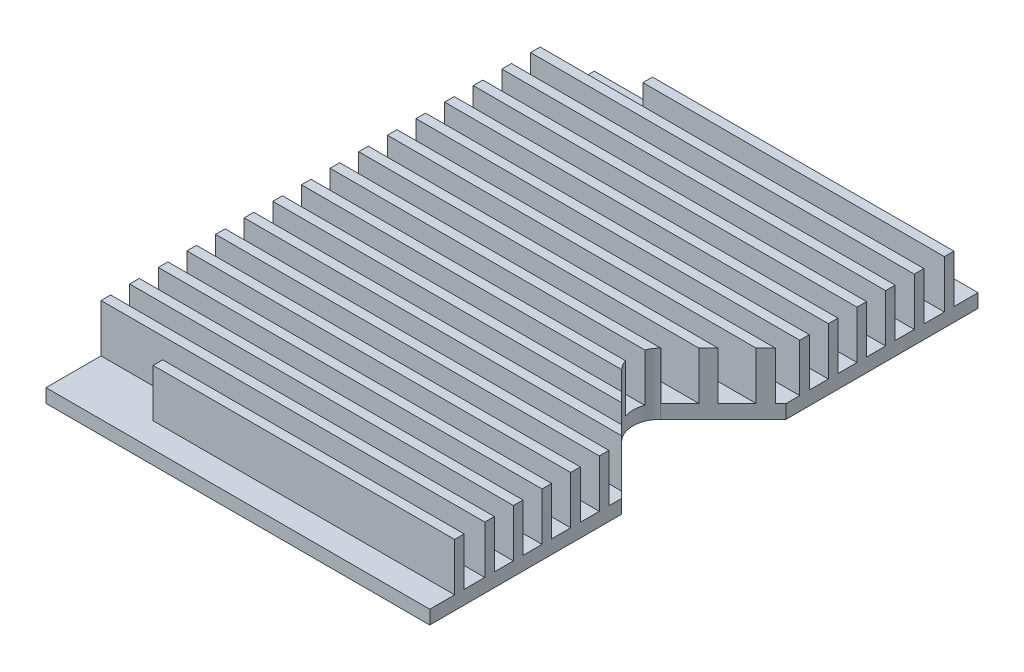
SolidWorks part; units mm, degrees
material "铜"
ref_plane "前视基准面" through (0, 0, 0) normal (0, 0, 1) x (1, 0, 0)
ref_plane "上视基准面" through (0, 0, 0) normal (0, 1, 0) x (1, 0, 0)
ref_plane "右视基准面" through (0, 0, 0) normal (1, 0, 0) x (0, 0, -1)
sketch "草图1" plane through (0, 0, 0) normal (0, 1, 0) x (1, 0, 0)
  line L1 (14, 20) -> (-14, 20)
  line L2 (14, 20) -> (14, -20)
  line L3 (14, -20) -> (-14, -20)
  line L4 (-14, 20) -> (-14, -20)
  line L5 (14, 20) -> (-14, -20) construction
  line L6 (14, -20) -> (-14, 20) construction
  point P0 (0, 0)
  dimension "D1" = 28
  dimension "D2" = 40
extrude "凸台-拉伸1" add sketch "草图1" along normal blind 1
sketch "草图2" plane through (0, 1, 0) normal (0, 1, 0) x (1, 0, 0)
  line L1 (-14, 20) -> (-14, -20) construction
  line L2 (-14, 15.35) -> (14, 15.35)
  line L3 (-14, 15.35) -> (-14, 16.05)
  line L4 (-14, 16.05) -> (14, 16.05)
  line L5 (14, 15.35) -> (14, 16.05)
  line L6 (14, -20) -> (14, 20) construction
  line L7 (14, 20) -> (-14, 20) construction
  line L8 (-14, 13.2609) -> (14, 13.2609)
  line L9 (-14, 13.9609) -> (14, 13.9609)
  line L10 (-14, 13.2609) -> (-14, 13.9609)
  line L11 (14, 13.2609) -> (14, 13.9609)
  line L12 (-14, 11.1719) -> (14, 11.1719)
  line L13 (-14, 11.8719) -> (14, 11.8719)
  line L14 (-14, 11.1719) -> (-14, 11.8719)
  line L15 (14, 11.1719) -> (14, 11.8719)
  line L16 (-14, 9.0828) -> (14, 9.0828)
  line L17 (-14, 9.7828) -> (14, 9.7828)
  line L18 (-14, 9.0828) -> (-14, 9.7828)
  line L19 (14, 9.0828) -> (14, 9.7828)
  line L20 (-14, 6.9937) -> (14, 6.9937)
  line L21 (-14, 7.6937) -> (14, 7.6937)
  line L22 (-14, 6.9937) -> (-14, 7.6937)
  line L23 (14, 6.9937) -> (14, 7.6937)
  line L24 (-14, 4.9047) -> (14, 4.9047)
  line L25 (-14, 5.6047) -> (14, 5.6047)
  line L26 (-14, 4.9047) -> (-14, 5.6047)
  line L27 (14, 4.9047) -> (14, 5.6047)
  line L28 (-14, 2.8156) -> (14, 2.8156)
  line L29 (-14, 3.5156) -> (14, 3.5156)
  line L30 (-14, 2.8156) -> (-14, 3.5156)
  line L31 (14, 2.8156) -> (14, 3.5156)
  line L32 (-14, 0.7265) -> (14, 0.7265)
  line L33 (-14, 1.4265) -> (14, 1.4265)
  line L34 (-14, 0.7265) -> (-14, 1.4265)
  line L35 (14, 0.7265) -> (14, 1.4265)
  line L36 (-14, -1.3625) -> (14, -1.3625)
  line L37 (-14, -0.6625) -> (14, -0.6625)
  line L38 (-14, -1.3625) -> (-14, -0.6625)
  line L39 (14, -1.3625) -> (14, -0.6625)
  line L40 (-14, -3.4516) -> (14, -3.4516)
  line L41 (-14, -2.7516) -> (14, -2.7516)
  line L42 (-14, -3.4516) -> (-14, -2.7516)
  line L43 (14, -3.4516) -> (14, -2.7516)
  line L44 (-14, -5.5407) -> (14, -5.5407)
  line L45 (-14, -4.8407) -> (14, -4.8407)
  line L46 (-14, -5.5407) -> (-14, -4.8407)
  line L47 (14, -5.5407) -> (14, -4.8407)
  line L48 (-14, -7.6297) -> (14, -7.6297)
  line L49 (-14, -6.9297) -> (14, -6.9297)
  line L50 (-14, -7.6297) -> (-14, -6.9297)
  line L51 (14, -7.6297) -> (14, -6.9297)
  line L52 (-14, -9.7188) -> (14, -9.7188)
  line L53 (-14, -9.0188) -> (14, -9.0188)
  line L54 (-14, -9.7188) -> (-14, -9.0188)
  line L55 (14, -9.7188) -> (14, -9.0188)
  line L56 (-14, -11.8078) -> (14, -11.8078)
  line L57 (-14, -11.1078) -> (14, -11.1078)
  line L58 (-14, -11.8078) -> (-14, -11.1078)
  line L59 (14, -11.8078) -> (14, -11.1078)
  line L60 (-14, -13.8969) -> (14, -13.8969)
  line L61 (-14, -13.1969) -> (14, -13.1969)
  line L62 (-14, -13.8969) -> (-14, -13.1969)
  line L63 (14, -13.8969) -> (14, -13.1969)
  line L64 (-14, -15.986) -> (14, -15.986)
  line L65 (-14, -15.286) -> (14, -15.286)
  line L66 (-14, -15.986) -> (-14, -15.286)
  line L67 (14, -15.986) -> (14, -15.286)
  line L69 (14, 17.55) -> (-8, 17.55)
  line L70 (14, 17.55) -> (14, 18.25)
  line L71 (14, 18.25) -> (-8, 18.25)
  line L72 (-8, 17.55) -> (-8, 18.25)
  line L73 (-8, -17.486) -> (14, -17.486)
  line L74 (-8, -17.486) -> (-8, -18.186)
  line L75 (-8, -18.186) -> (14, -18.186)
  line L76 (14, -17.486) -> (14, -18.186)
  dimension "D1" = 4.65
  dimension "D2" = 0.7
  dimension "D4" = 0.7
  dimension "D5" = 1.5
  dimension "D6" = 1.5
  dimension "D7" = 0.7
  dimension "D8" = 22
  dimension "D9" = 22
  dimension "D3" = 16
extrude "凸台-拉伸2" add sketch "草图2" along normal blind 3.5
sketch "草图4" plane through (0, 0, 0) normal (0, -1, 0) x (1, 0, 0)
  line L0 (14, 0) -> (14, 6)
  line L3 (14, 20) -> (14, -20) construction
  line L4 (14, 6) -> (8, 0)
  line L5 (-36, 0) -> (59.1286, 0) construction
  line L8 (8, 0) -> (14, 0)
  line L9 (8, 0) -> (14, -6)
  line L10 (14, -6) -> (14, 0)
  circle A0 centre (10.8284, 0) radius 2
  line M8 (14, -20) -> (14, 20)
  dimension "D2" = 6
  dimension "D4" = 4
  dimension "D1" = 6
  dimension "D3" = 6
extrude "切除-拉伸1" cut sketch "草图4" against normal through all contours L8 A0 L10 | A0 L8 M8 | A0 L0 L4 | A0 L9 M8
